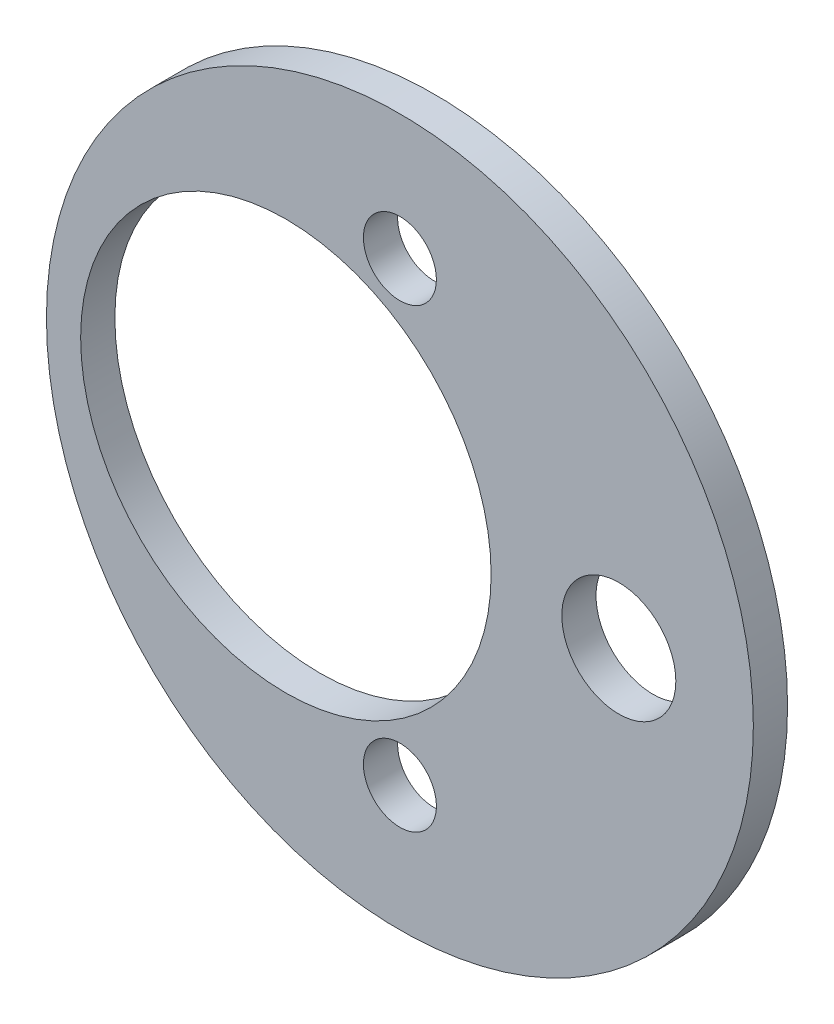
SolidWorks part; units mm, degrees
material "AISI 304"
ref_plane "Спереди" through (0, 0, 0) normal (0, 0, 1) x (1, 0, 0)
ref_plane "Сверху" through (0, 0, 0) normal (0, 1, 0) x (1, 0, 0)
ref_plane "Справа" through (0, 0, 0) normal (1, 0, 0) x (0, 0, -1)
sketch "Эскиз1" plane through (0, 0, 0) normal (0, 0, 1) x (1, 0, 0)
  line L0 (-19.15, 0) -> (18.4889, 0) construction
  line L3 (0, 17.4039) -> (0, -17.1885) construction
  circle A23 centre (0, 0) radius 15.5
  circle A24 centre (-5, 0) radius 9
  circle A25 centre (9.6, 0) radius 2.5
  circle A26 centre (0, 10) radius 1.6
  circle A27 centre (0, -10) radius 1.6
  dimension "D1" = 31
  dimension "D2" = 5
  dimension "D3" = 18
  dimension "D6" = 3.2
  dimension "D7" = 10
  dimension "D5" = 5
  dimension "D4" = 9.6
extrude "Бобышка-Вытянуть1" add sketch "Эскиз1" along normal blind 1.5
